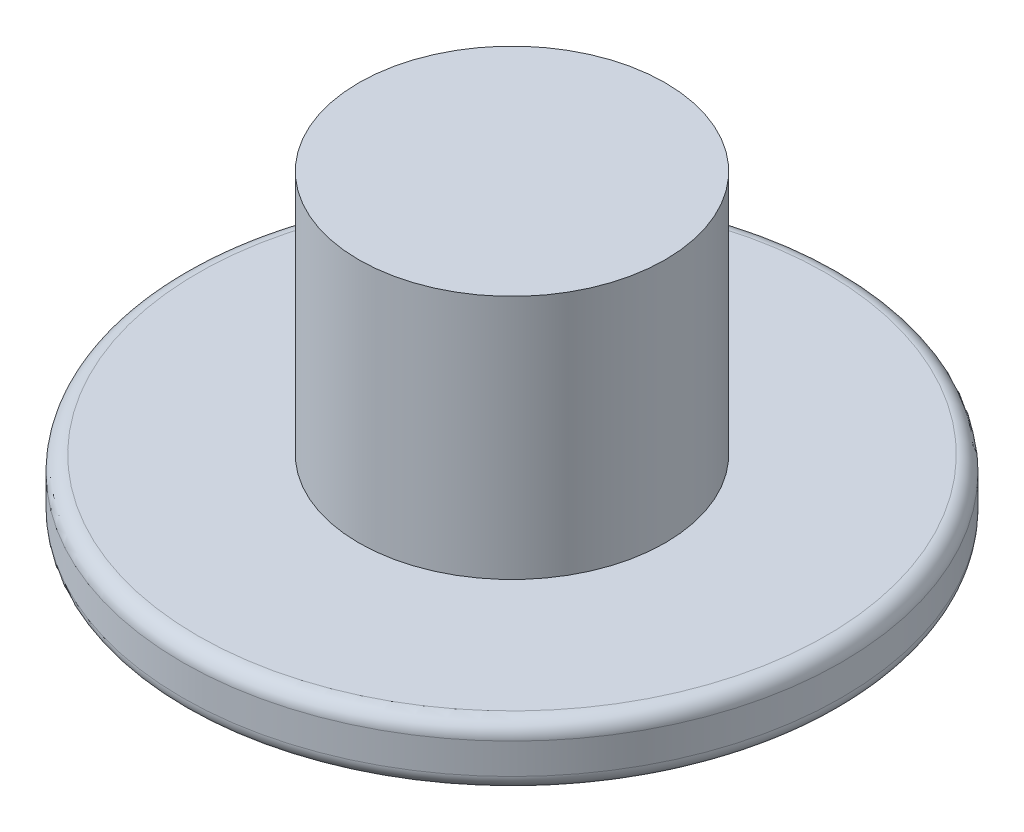
SolidWorks part; units mm, degrees
ref_plane "Front Plane" through (0, 0, 0) normal (0, 0, 1) x (1, 0, 0)
ref_plane "Top Plane" through (0, 0, 0) normal (0, 1, 0) x (1, 0, 0)
ref_plane "Right Plane" through (0, 0, 0) normal (1, 0, 0) x (0, 0, -1)
sketch "Sketch1" plane through (0, 0, 0) normal (0, 1, 0) x (1, 0, 0)
  circle A4 centre (-5.4087, -40.3067) radius 10.75
  circle A12 centre (-5.4087, -40.3067) radius 4.9321
  dimension "D5" = 21.5
extrude "Boss-Extrude5" add sketch "Sketch1" along normal blind 2 contours A4
sketch "Sketch4" plane through (0, 2, 0) normal (0, 1, 0) x (1, 0, 0)
  circle A0 centre (-5.4087, -40.3067) radius 5
  circle A1 centre (-5.4087, -40.3067) radius 10.75 construction
extrude "Boss-Extrude6" add sketch "Sketch4" along normal blind 8
sketch "Sketch5" plane through (0, 0, 0) normal (0, -1, 0) x (1, 0, 0)
  text T0 "<b>5</b>" font "Century Gothic" height 10
extrude "Cut-Extrude2" cut sketch "Sketch5" against normal blind 0.5
fillet "Fillet1" radius 0.5 2 edges at (-5.4087, 2, 51.0567) (-5.4087, 0, 51.0567)
